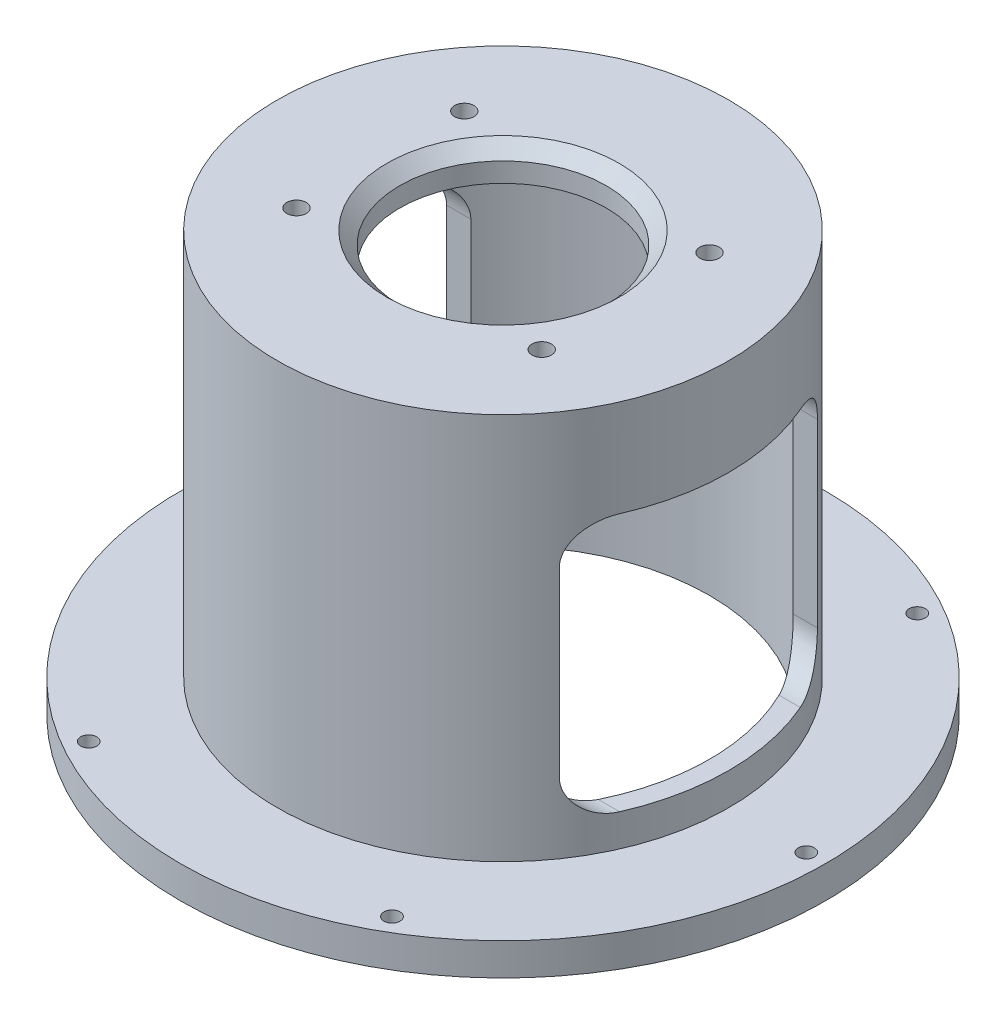
SolidWorks part; units mm, degrees
material "1060 合金"
ref_plane "前视基准面" through (0, 0, 0) normal (0, 0, 1) x (1, 0, 0)
ref_plane "上视基准面" through (0, 0, 0) normal (0, 1, 0) x (1, 0, 0)
ref_plane "右视基准面" through (0, 0, 0) normal (1, 0, 0) x (0, 0, -1)
sketch "草图1" plane through (0, 0, 0) normal (1, 0, 0) x (0, 0, -1)
  line L0 (0, 0) -> (0, 130.9321) construction
  line L1 (32, 0) -> (50, 0)
  line L2 (50, 0) -> (50, 5)
  line L3 (50, 5) -> (35, 5)
  line L4 (35, 5) -> (35, 65)
  line L5 (35, 65) -> (16, 65)
  line L6 (16, 65) -> (16, 60)
  line L7 (16, 60) -> (32, 60)
  line L8 (32, 60) -> (32, 0)
  dimension "D1" = 3
  dimension "D2" = 50
  dimension "D3" = 60
  dimension "D4" = 35
  dimension "D5" = 5
  dimension "D6" = 16
  dimension "D7" = 5
revolve "旋转1" add sketch "草图1" angle 360 about L0
chamfer "倒角1" distance 2 angle 45 1 edges at (0, 65, -16)
hole_wizard "M3 间隙孔1" positions "草图3" profile "草图2" hole size "M3" standard "GB" end condition up to next
sketch "草图3" plane through (0, 65, 0) normal (0, 1, 0) x (1, 0, 0)
  line L1 (-19, 13) -> (19, 13) construction
  line L2 (-19, 13) -> (-19, -13) construction
  line L3 (-19, -13) -> (19, -13) construction
  line L4 (19, 13) -> (19, -13) construction
  line L5 (-19, 13) -> (19, -13) construction
  line L6 (-19, -13) -> (19, 13) construction
  point P2 (19, -13)
  point P79 (-19, 13)
  point P80 (-19, -13)
  point P81 (19, 13)
  dimension "D1" = 38
  dimension "D2" = 26
sketch "草图2" plane through (19, 65, 13) normal (1, 0, 0) x (0, 0, 1)
  line L0 (0, 0) -> (0, 5)
  line L1 (0, 5) -> (1.5, 5)
  line L2 (1.5, 5) -> (1.5, 0)
  line L5 (1.5, 0) -> (0, 0)
  line L11 (0, -6.35) -> (0, 107.95) construction
  dimension "通孔孔直径" = 3
  dimension "通孔孔深度" = 5
sketch "草图4" plane through (0, 0, 0) normal (1, 0, 0) x (0, 0, -1)
  line L0 (0, 0) -> (0, 79.8308) construction
  line L1 (35, 65) -> (-35, 65) construction
  line L2 (-14, 10) -> (14, 10)
  line L3 (-20, 16) -> (-20, 44)
  line L4 (-14, 50) -> (14, 50)
  line L5 (20, 16) -> (20, 44)
  line L6 (-20, 10) -> (20, 50) construction
  line L7 (-20, 50) -> (20, 10) construction
  arc A0 (-14, 10) -> (-20, 16) centre (-14, 16) cw
  arc A1 (14, 10) -> (20, 16) centre (14, 16) ccw
  arc A2 (14, 50) -> (20, 44) centre (14, 44) cw
  arc A3 (-20, 44) -> (-14, 50) centre (-14, 44) cw
  point P3 (0, 30)
  dimension "D4" = 6
  dimension "D1" = 15
  dimension "D2" = 40
  dimension "D3" = 40
extrude "切除-拉伸1" cut sketch "草图4" against normal through all both and the other way through all
hole_wizard "M3 螺纹孔1" positions "草图6" profile "草图5" tap size "M3" standard "GB" end condition up to next
sketch "草图6" plane through (0, 0, 0) normal (0, -1, 0) x (-1, 0, 0)
  circle A0 centre (0, 0) radius 47 construction
  point P6 (47, 0)
  point P14 (23.5, -40.7032)
  point P15 (-23.5, -40.7032)
  point P16 (-47, 0)
  point P17 (-23.5, 40.7032)
  point P18 (23.5, 40.7032)
  dimension "D1" = 94
  dimension "D2" = 6
sketch "草图5" plane through (-47, 0, 0) normal (1, 0, 0) x (0, 0, -1)
  line L0 (0, 0) -> (0, 5)
  line L1 (0, 5) -> (1.25, 5)
  line L2 (1.25, 5) -> (1.25, 0)
  line L5 (1.25, 0) -> (0, 0)
  line L11 (0, -6.35) -> (0, 107.95) construction
  dimension "螺纹线主直径" = 2.5
  dimension "通孔螺纹孔钻头深度" = 5
